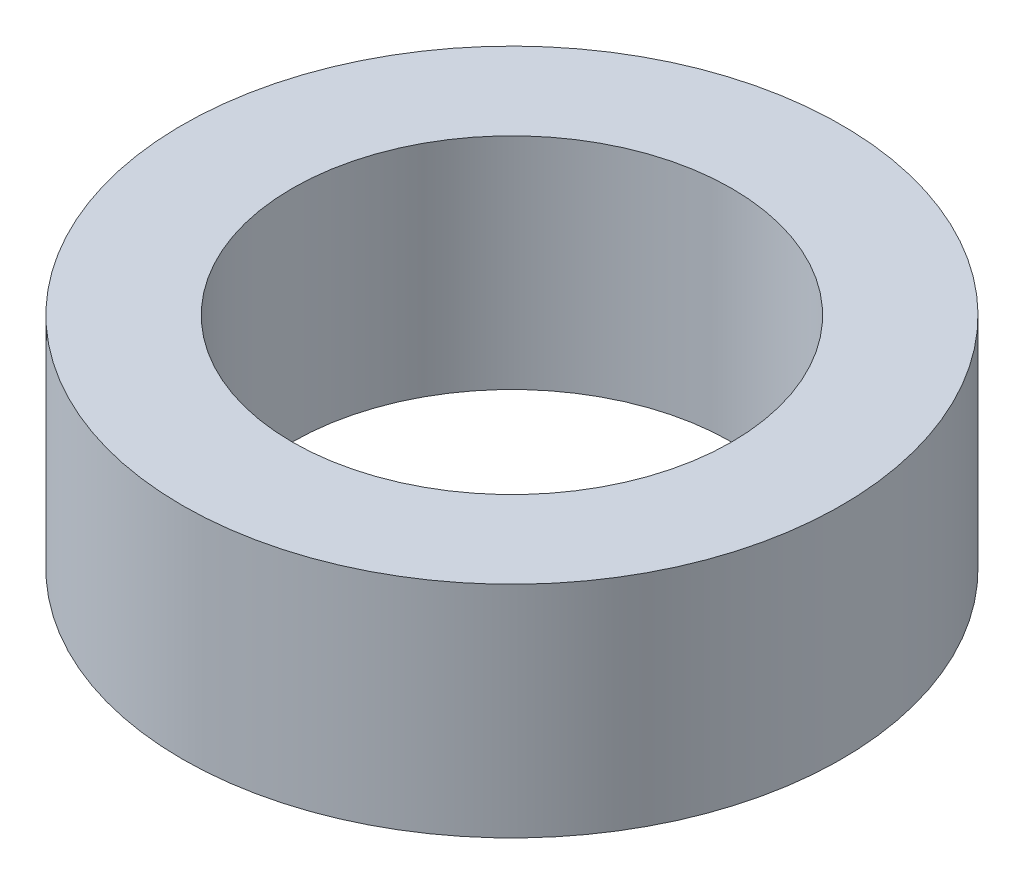
SolidWorks part; units mm, degrees
ref_plane "Front Plane" through (0, 0, 0) normal (0, 0, 1) x (1, 0, 0)
ref_plane "Top Plane" through (0, 0, 0) normal (0, 1, 0) x (1, 0, 0)
ref_plane "Right Plane" through (0, 0, 0) normal (1, 0, 0) x (0, 0, -1)
sketch "Sketch1" plane through (0, 0, 0) normal (0, 1, 0) x (1, 0, 0)
  circle A0 centre (0, 0) radius 3
  circle A1 centre (0, 0) radius 4.5
extrude "Boss-Extrude1" add sketch "Sketch1" along normal blind 3
